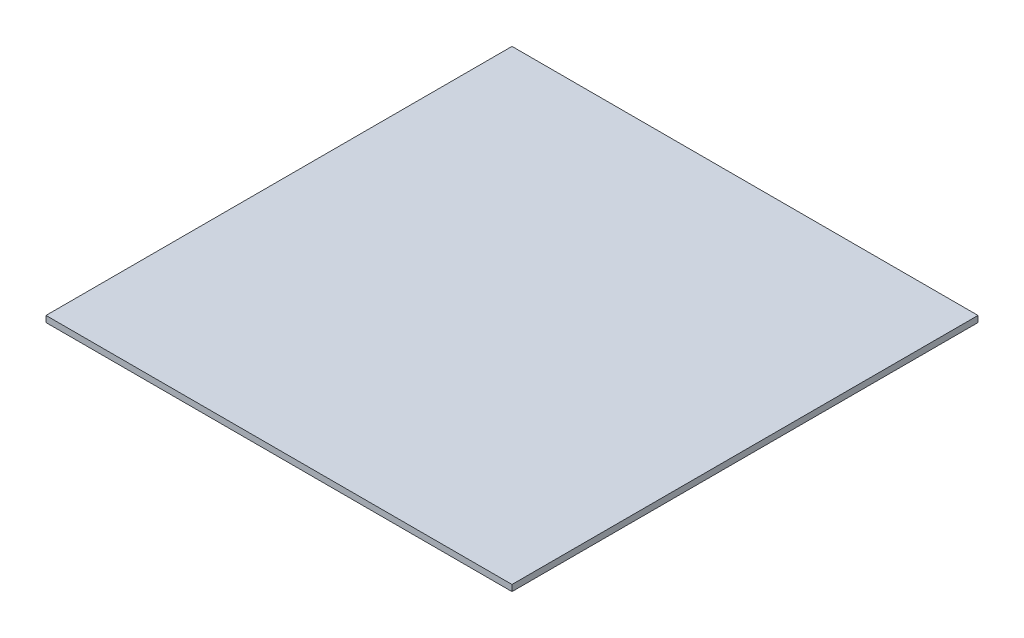
SolidWorks part; units mm, degrees
ref_plane "Front Plane" through (0, 0, 0) normal (0, 0, 1) x (1, 0, 0)
ref_plane "Top Plane" through (0, 0, 0) normal (0, 1, 0) x (1, 0, 0)
ref_plane "Right Plane" through (0, 0, 0) normal (1, 0, 0) x (0, 0, -1)
sketch "Sketch1" plane through (0, 0, 0) normal (0, 1, 0) x (1, 0, 0)
  line L1 (-75, 75) -> (75, 75)
  line L2 (-75, 75) -> (-75, -75)
  line L3 (-75, -75) -> (75, -75)
  line L4 (75, 75) -> (75, -75)
  line L5 (-75, 75) -> (75, -75) construction
  line L6 (-75, -75) -> (75, 75) construction
  point P0 (0, 0)
  dimension "D1" = 150
  dimension "D2" = 150
extrude "Boss-Extrude1" add sketch "Sketch1" along normal blind 2
